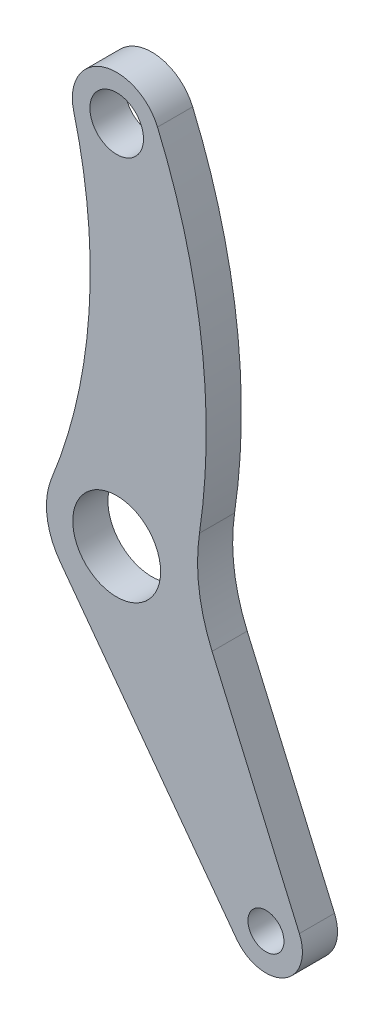
SolidWorks part; units mm, degrees
material "Thornel Mat VMA"
ref_plane "前视基准面" through (0, 0, 0) normal (0, 0, 1) x (1, 0, 0)
ref_plane "上视基准面" through (0, 0, 0) normal (0, 1, 0) x (1, 0, 0)
ref_plane "右视基准面" through (0, 0, 0) normal (1, 0, 0) x (0, 0, -1)
sketch "草图1" plane through (0, 0, 0) normal (0, 0, 1) x (1, 0, 0)
  line L0 (0, 0) -> (0, 20.85) construction
  line L1 (0, 0) -> (8.5, -14.7224) construction
  line L2 (-2.5187, 21.0286) -> (-3.99, 0.283)
  line L3 (2.5187, 21.0286) -> (3.9415, 0.9665)
  line L4 (-3.2154, -2.3794) -> (6.832, -15.9567)
  line L5 (3.9415, 0.9665) -> (10.4029, -13.8951)
  circle A0 centre (0, 20.85) radius 1.525
  circle A1 centre (8.5, -14.7224) radius 1.025
  circle A2 centre (0, 0) radius 2.5
  arc A3 (2.5187, 21.0286) -> (-2.5187, 21.0286) centre (0, 20.85) ccw
  arc A4 (-3.99, 0.283) -> (-3.2154, -2.3794) centre (0, 0) ccw
  arc A5 (6.832, -15.9567) -> (10.4029, -13.8951) centre (8.5, -14.7224) ccw
  dimension "D4" = 5
  dimension "D5" = 2.05
  dimension "D6" = 3.05
  dimension "D7" = 1
  dimension "D8" = 8
  dimension "D9" = 1.05
  dimension "D1" = 150
  dimension "D2" = 20.85
  dimension "D3" = 17
extrude "凸台-拉伸1" add sketch "草图1" along normal blind 2
sketch "草图2" plane through (0, 0, 2) normal (0, 0, 1) x (1, 0, 0)
  line L0 (-2.5187, 21.0286) -> (-3.99, 0.283)
  arc A0 (-2.5187, 21.0286) -> (-2.446, 20.2234) centre (0, 20.85) ccw
  arc A3 (-3.7068, 1.5033) -> (-3.99, 0.283) centre (0, 0) ccw
  arc A4 (-2.446, 20.2234) -> (-3.7068, 1.5033) centre (-31.5075, 12.7781) cw
  dimension "D3" = 30
extrude "切除-拉伸1" cut sketch "草图2" against normal blind 10
sketch "草图3" plane through (0, 0, 2) normal (0, 0, 1) x (1, 0, 0)
  line L0 (0, 4) -> (0, 18.325)
  arc A0 (0, 18.325) -> (2.3249, 21.8351) centre (0, 20.85) ccw
  arc A1 (3.8582, -1.0555) -> (0, 4) centre (0, 0) ccw
  arc A2 (2.3249, 21.8351) -> (3.8582, -1.0555) centre (-29.9014, 8.1798) cw
  dimension "D1" = 8
  dimension "D2" = 5.05
  dimension "D3" = 35
extrude "凸台-拉伸2" add sketch "草图3" against normal up to surface (2 mm away) up to face at (1.525, 20.85, 0)
fillet "圆角1" radius 10 1 edges at (4.2109, 0.3469, 1)
